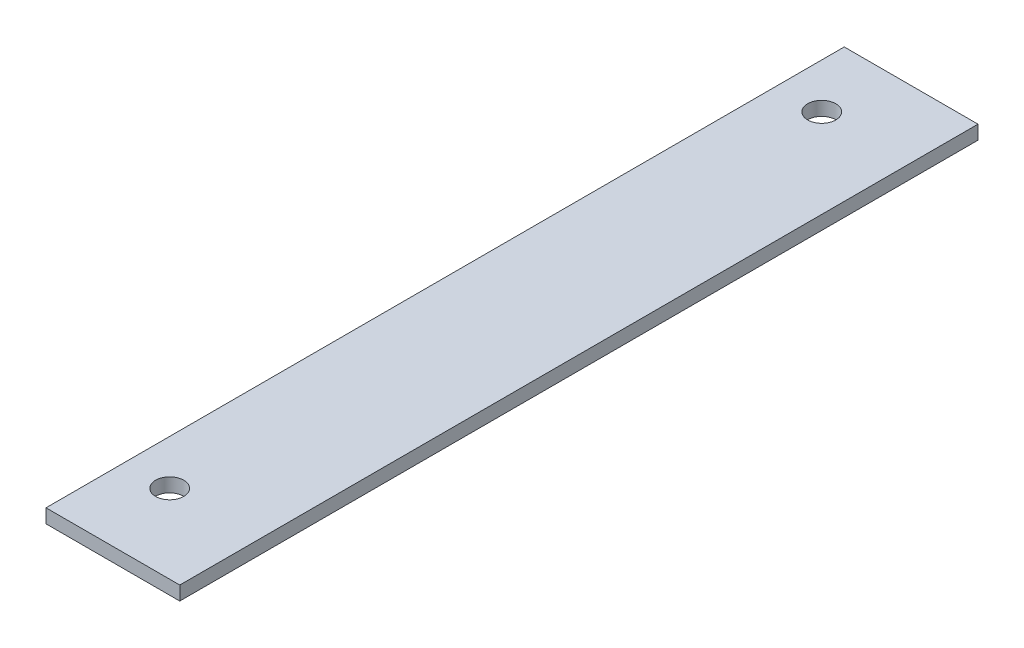
SolidWorks part; units mm, degrees
material "E-Glass Fiber"
ref_plane "Front Plane" through (0, 0, 0) normal (0, 0, 1) x (1, 0, 0)
ref_plane "Top Plane" through (0, 0, 0) normal (0, 1, 0) x (1, 0, 0)
ref_plane "Right Plane" through (0, 0, 0) normal (1, 0, 0) x (0, 0, -1)
sketch "Sketch1" plane through (0, 0, 0) normal (0, 1, 0) x (1, 0, 0)
  line L1 (-7.555, -45.085) -> (7.555, -45.085)
  line L2 (-7.555, -45.085) -> (-7.555, 45.085)
  line L3 (-7.555, 45.085) -> (7.555, 45.085)
  line L4 (7.555, -45.085) -> (7.555, 45.085)
  line L5 (-7.555, -45.085) -> (7.555, 45.085) construction
  line L6 (-7.555, 45.085) -> (7.555, -45.085) construction
  point P0 (0, 0)
  dimension "D1" = 90.17
  dimension "D2" = 15.11
extrude "Boss-Extrude1" add sketch "Sketch1" along normal blind 1.57
sketch "Sketch2" plane through (0, 1.57, 0) normal (0, 1, 0) x (1, 0, 0)
  line L0 (-7.555, -45.085) -> (7.555, -45.085) construction
  line L1 (-7.555, 45.085) -> (-7.555, -45.085) construction
  circle A0 centre (-2.475, -36.195) radius 1.59
  circle A1 centre (-2.475, 37.465) radius 1.59
  point P8 (-59.5228, 19.3859)
  dimension "D1" = 3.18
  dimension "D2" = 3.18
  dimension "D3" = 8.89
  dimension "D4" = 5.08
  dimension "D5" = 5.08
  dimension "D6" = 73.66
extrude "Cut-Extrude1" cut sketch "Sketch2" against normal through all
